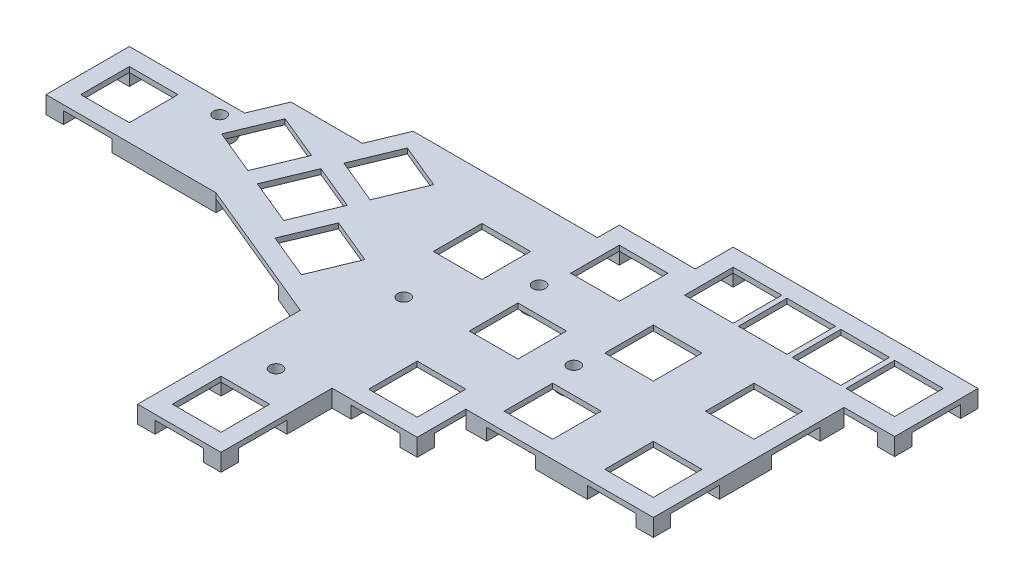
SolidWorks part; units mm, degrees
ref_plane "Front Plane" through (0, 0, 0) normal (0, 0, 1) x (1, 0, 0)
ref_plane "Top Plane" through (0, 0, 0) normal (0, 1, 0) x (1, 0, 0)
ref_plane "Right Plane" through (0, 0, 0) normal (1, 0, 0) x (0, 0, -1)
sketch "Button Reference" plane through (0, 0, 0) normal (0, 1, 0) x (1, 0, 0)
  line L0 (24.5, 61) -> (24.5, 32) construction
  line L1 (-36.2591, 48.1292) -> (-29.3708, 64.7591) construction
  line L2 (49.5, 75) -> (49.5, 46) construction
  line L3 (78.5, 75) -> (78.5, 46) construction
  line L4 (17.5, 0) -> (-17.5, 0) construction
  line L5 (-36.2591, 48.1292) -> (-19.6292, 41.2409) construction
  line L6 (17.5, -12.5) -> (-17.5, -12.5)
  line L7 (17.5, 12.5) -> (-17.5, 12.5)
  line L8 (24.6803, 89.9994) -> (49.5, 75) construction
  line L9 (24.6803, 89.9994) -> (24.5, 61) construction
  line L10 (-0.5241, 75.6559) -> (24.6803, 89.9994) construction
  line L11 (-0.5241, 75.6559) -> (24.5, 61) construction
  line L12 (-29.3708, 64.7591) -> (-12.7409, 57.8708) construction
  line L13 (-19.6292, 41.2409) -> (-12.7409, 57.8708) construction
  line L14 (-36.2591, 48.1292) -> (-12.7409, 57.8708) construction
  line L15 (-29.3708, 64.7591) -> (-19.6292, 41.2409) construction
  line L16 (-35.6984, 52.2266) -> (-28.8101, 68.8564) construction
  line L17 (-35.6984, 52.2266) -> (-52.3282, 59.1149) construction
  line L18 (-28.8101, 68.8564) -> (-45.4399, 75.7447) construction
  line L19 (-52.3282, 59.1149) -> (-45.4399, 75.7447) construction
  line L20 (-35.6984, 52.2266) -> (-45.4399, 75.7447) construction
  line L21 (-28.8101, 68.8564) -> (-52.3282, 59.1149) construction
  line L22 (-69.9281, 66.405) -> (-63.0398, 83.0348) construction
  line L23 (-69.9281, 66.405) -> (-53.2983, 59.5167) construction
  line L24 (-63.0398, 83.0348) -> (-46.41, 76.1465) construction
  line L25 (-53.2983, 59.5167) -> (-46.41, 76.1465) construction
  line L26 (-69.9281, 66.405) -> (-46.41, 76.1465) construction
  line L27 (-63.0398, 83.0348) -> (-53.2983, 59.5167) construction
  line L28 (-40.5692, 63.9856) -> (-22.9693, 56.6955) construction
  line L29 (-40.5692, 63.9856) -> (-58.1691, 71.2758) construction
  line L30 (-45.0381, 76.7148) -> (-38.1498, 93.3446) construction
  line L31 (-45.0381, 76.7148) -> (-28.4083, 69.8265) construction
  line L32 (-38.1498, 93.3446) -> (-21.52, 86.4563) construction
  line L33 (-28.4083, 69.8265) -> (-21.52, 86.4563) construction
  line L34 (-45.0381, 76.7148) -> (-21.52, 86.4563) construction
  line L35 (-38.1498, 93.3446) -> (-28.4083, 69.8265) construction
  line L36 (-40.5692, 63.9856) -> (-33.2791, 81.5855) construction
  line L37 (-24.5, 53) -> (-22.9693, 56.6955) construction
  line L38 (-58.1691, 71.2758) -> (-65.4592, 53.6759) construction
  line L39 (-65.4592, 53.6759) -> (-90.4039, 64.0083) construction
  line L40 (-70.5814, 66.1344) -> (-63.3104, 83.6881)
  line L41 (-63.3104, 83.6881) -> (-45.7105, 76.398)
  line L42 (-45.7105, 76.398) -> (-38.4204, 93.9979)
  line L43 (-38.4204, 93.9979) -> (-20.8667, 86.7269)
  line L44 (-20.8667, 86.7269) -> (-29.6876, 65.4315)
  line L45 (-29.6876, 65.4315) -> (-12.0877, 58.1414)
  line L46 (-12.0877, 58.1414) -> (-19.3586, 40.5877)
  line L47 (-19.3586, 40.5877) -> (-36.9123, 47.8586)
  line L48 (-36.9123, 47.8586) -> (-35.3816, 51.5542)
  line L49 (-35.3816, 51.5542) -> (-70.5814, 66.1344)
  line L50 (-66.484, 74.7199) -> (-66.9459, 74.9112) construction
  line L51 (-29.6436, 90.3624) -> (-29.8349, 89.9005) construction
  line L52 (-16.1851, 49.5558) -> (-15.7231, 49.3645) construction
  line L53 (-33.2791, 81.8539) -> (-33.2791, 81.5855) construction
  line L54 (46.566, 100.92) -> (46.566, 75) construction
  line L55 (46.566, 75) -> (49.5, 75) construction
  circle A0 centre (24.5, 32) radius 12.5
  circle A1 centre (24.5, 61) radius 12.5
  circle A2 centre (49.5, 46) radius 12.5
  circle A3 centre (49.5, 75) radius 12.5
  circle A4 centre (78.5, 75) radius 12.5
  circle A5 centre (78.5, 46) radius 12.5
  arc A6 (17.5, -12.5) -> (17.5, 12.5) centre (17.5, 0) ccw
  arc A7 (-17.5, 12.5) -> (-17.5, -12.5) centre (-17.5, 0) ccw
  circle A8 centre (-90.4039, 64.0083) radius 15.5
  circle A9 centre (24.6803, 89.9994) radius 12.5
  circle A10 centre (-0.5241, 75.6559) radius 12.5
  circle A11 centre (46.566, 100.92) radius 2.8
  circle A12 centre (62.066, 100.92) radius 2.8
  circle A13 centre (77.566, 100.92) radius 2.8
  circle A14 centre (93.066, 100.92) radius 2.8
  point P1 (-24.5, 53)
  point P3 (-40.5692, 63.9856)
  point P4 (-58.1691, 71.2758)
  point P35 (0, 0)
  point P43 (-33.2791, 81.5855)
  point P50 (-30, 0)
  point P51 (30, 0)
  dimension "D2" = 25
  dimension "D6" = 12.5
  dimension "D10" = 31
  dimension "D26" = 5.6
  dimension "D1" = 29
  dimension "D3" = 25
  dimension "D4" = 29
  dimension "D5" = 14
  dimension "D7" = 32
  dimension "D8" = 7
  dimension "D9" = 60
  dimension "D11" = 29
  dimension "D12" = 29
  dimension "D13" = 7
  dimension "D14" = 18
  dimension "D15" = 27
  dimension "D16" = 19.05
  dimension "D17" = 19.05
  dimension "D18" = 53
  dimension "D19" = 4
  dimension "D20" = 0.5
  dimension "D21" = 0.5
  dimension "D22" = 0.5
  dimension "D23" = 0.5
  dimension "D24" = 0.5
  dimension "D25" = 22.5
  dimension "D27" = 15.5
  dimension "D28" = 15.5
  dimension "D29" = 15.5
  dimension "D30" = 25.92
  dimension "D31" = 2.934
sketch "Sketch2" plane through (0, 0, 0) normal (0, 1, 0) x (1, 0, 0)
  line L0 (90.5, 34) -> (90.5, 88.92)
  line L1 (-97.4039, 57.0083) -> (-83.4039, 57.0083)
  line L2 (-97.4039, 57.0083) -> (-97.4039, 71.0083)
  line L3 (-97.4039, 71.0083) -> (-83.4039, 71.0083)
  line L4 (-83.4039, 57.0083) -> (-83.4039, 71.0083)
  line L5 (-97.4039, 57.0083) -> (-83.4039, 71.0083) construction
  line L6 (-97.4039, 71.0083) -> (-83.4039, 57.0083) construction
  line L11 (-67.315, 67.4874) -> (-61.9574, 80.4217)
  line L12 (-67.315, 67.4874) -> (-54.3807, 62.1298)
  line L17 (-61.9574, 80.4217) -> (-49.0231, 75.0641)
  line L18 (-54.3807, 62.1298) -> (-49.0231, 75.0641)
  line L23 (-67.315, 67.4874) -> (-49.0231, 75.0641) construction
  line L24 (-61.9574, 80.4217) -> (-54.3807, 62.1298) construction
  line L25 (53.566, 93.92) -> (39.566, 93.92)
  line L30 (-31.4232, 67.774) -> (-44.3575, 73.1316)
  line L31 (-31.4232, 67.774) -> (-36.7808, 54.8397)
  line L32 (53.566, 93.92) -> (53.566, 107.92)
  line L33 (-7.5241, 68.6559) -> (6.4759, 68.6559)
  line L34 (-7.5241, 68.6559) -> (-7.5241, 82.6559)
  line L35 (-7.5241, 82.6559) -> (6.4759, 82.6559)
  line L36 (6.4759, 68.6559) -> (6.4759, 82.6559)
  line L37 (-7.5241, 68.6559) -> (6.4759, 82.6559) construction
  line L38 (-7.5241, 82.6559) -> (6.4759, 68.6559) construction
  line L39 (17.6803, 82.9994) -> (31.6803, 82.9994)
  line L40 (17.6803, 82.9994) -> (17.6803, 96.9994)
  line L41 (17.6803, 96.9994) -> (31.6803, 96.9994)
  line L42 (31.6803, 82.9994) -> (31.6803, 96.9994)
  line L43 (17.6803, 82.9994) -> (31.6803, 96.9994) construction
  line L44 (17.6803, 96.9994) -> (31.6803, 82.9994) construction
  line L45 (17.5, 68) -> (31.5, 68)
  line L46 (17.5, 68) -> (17.5, 54)
  line L47 (17.5, 54) -> (31.5, 54)
  line L48 (31.5, 68) -> (31.5, 54)
  line L49 (17.5, 68) -> (31.5, 54) construction
  line L50 (17.5, 54) -> (31.5, 68) construction
  line L51 (17.5, 39) -> (31.5, 39)
  line L52 (17.5, 39) -> (17.5, 25)
  line L53 (17.5, 25) -> (31.5, 25)
  line L54 (31.5, 39) -> (31.5, 25)
  line L55 (17.5, 39) -> (31.5, 25) construction
  line L56 (17.5, 25) -> (31.5, 39) construction
  line L57 (42.5, 39) -> (56.5, 39)
  line L58 (42.5, 39) -> (42.5, 53)
  line L59 (42.5, 53) -> (56.5, 53)
  line L60 (56.5, 39) -> (56.5, 53)
  line L61 (42.5, 39) -> (56.5, 53) construction
  line L62 (42.5, 53) -> (56.5, 39) construction
  line L63 (42.5, 82) -> (56.5, 82)
  line L64 (42.5, 82) -> (42.5, 68)
  line L65 (42.5, 68) -> (56.5, 68)
  line L66 (56.5, 82) -> (56.5, 68)
  line L67 (42.5, 82) -> (56.5, 68) construction
  line L68 (42.5, 68) -> (56.5, 82) construction
  line L69 (71.5, 68) -> (85.5, 68)
  line L70 (71.5, 68) -> (71.5, 82)
  line L71 (71.5, 82) -> (85.5, 82)
  line L72 (85.5, 68) -> (85.5, 82)
  line L73 (71.5, 68) -> (85.5, 82) construction
  line L74 (71.5, 82) -> (85.5, 68) construction
  line L75 (71.5, 39) -> (85.5, 39)
  line L76 (71.5, 39) -> (71.5, 53)
  line L77 (71.5, 53) -> (85.5, 53)
  line L78 (85.5, 39) -> (85.5, 53)
  line L79 (71.5, 39) -> (85.5, 53) construction
  line L80 (71.5, 53) -> (85.5, 39) construction
  line L81 (-7, -7) -> (7, -7)
  line L82 (-7, -7) -> (-7, 7)
  line L83 (-7, 7) -> (7, 7)
  line L84 (7, -7) -> (7, 7)
  line L85 (-7, -7) -> (7, 7) construction
  line L86 (-7, 7) -> (7, -7) construction
  line L87 (53.566, 107.92) -> (39.566, 107.92)
  line L88 (-44.3575, 73.1316) -> (-49.7151, 60.1973)
  line L89 (-36.7808, 54.8397) -> (-49.7151, 60.1973)
  line L90 (-31.4232, 67.774) -> (-49.7151, 60.1973) construction
  line L91 (-44.3575, 73.1316) -> (-36.7808, 54.8397) construction
  line L92 (-33.6459, 49.2116) -> (-20.7116, 43.8541)
  line L93 (-33.6459, 49.2116) -> (-28.2884, 62.1459)
  line L94 (-20.7116, 43.8541) -> (-15.3541, 56.7884)
  line L95 (-28.2884, 62.1459) -> (-15.3541, 56.7884)
  line L96 (-33.6459, 49.2116) -> (-15.3541, 56.7884) construction
  line L97 (-20.7116, 43.8541) -> (-28.2884, 62.1459) construction
  line L98 (-42.425, 77.7972) -> (-37.0674, 90.7315)
  line L99 (-42.425, 77.7972) -> (-29.4907, 72.4396)
  line L100 (-37.0674, 90.7315) -> (-24.1331, 85.3739)
  line L101 (-29.4907, 72.4396) -> (-24.1331, 85.3739)
  line L102 (-42.425, 77.7972) -> (-24.1331, 85.3739) construction
  line L103 (-37.0674, 90.7315) -> (-29.4907, 72.4396) construction
  line L104 (-28.8101, 68.8564) -> (-45.4399, 75.7447) construction
  line L105 (39.566, 93.92) -> (39.566, 107.92)
  line L106 (53.566, 93.92) -> (39.566, 107.92) construction
  line L107 (53.566, 107.92) -> (39.566, 93.92) construction
  line L108 (55.066, 93.92) -> (69.066, 93.92)
  line L109 (55.066, 93.92) -> (55.066, 107.92)
  line L110 (55.066, 107.92) -> (69.066, 107.92)
  line L111 (69.066, 93.92) -> (69.066, 107.92)
  line L112 (55.066, 93.92) -> (69.066, 107.92) construction
  line L113 (55.066, 107.92) -> (69.066, 93.92) construction
  line L114 (70.566, 93.92) -> (84.566, 93.92)
  line L115 (70.566, 93.92) -> (70.566, 107.92)
  line L116 (70.566, 107.92) -> (84.566, 107.92)
  line L117 (84.566, 93.92) -> (84.566, 107.92)
  line L118 (70.566, 93.92) -> (84.566, 107.92) construction
  line L119 (70.566, 107.92) -> (84.566, 93.92) construction
  line L120 (86.066, 93.92) -> (100.066, 93.92)
  line L121 (86.066, 93.92) -> (86.066, 107.92)
  line L122 (86.066, 107.92) -> (100.066, 107.92)
  line L123 (100.066, 93.92) -> (100.066, 107.92)
  line L124 (86.066, 93.92) -> (100.066, 107.92) construction
  line L125 (86.066, 107.92) -> (100.066, 93.92) construction
  line L126 (105.066, 112.92) -> (34.566, 112.92)
  line L128 (12, -12) -> (-12, -12)
  line L129 (-102.4039, 76.0083) -> (-102.4039, 52.0083)
  line L130 (90.5, 88.92) -> (105.066, 88.92)
  line L131 (90.5, 34) -> (36.5, 34)
  line L132 (36.5, 34) -> (36.5, 20)
  line L133 (36.5, 20) -> (12, 20)
  line L134 (12, 20) -> (12, -12)
  line L135 (105.066, 112.92) -> (105.066, 88.92)
  line L136 (34.566, 112.92) -> (34.566, 101.9994)
  line L137 (34.566, 101.9994) -> (12.6803, 101.9994)
  line L138 (-40.4083, 95.7315) -> (-44.6788, 85.4217)
  line L139 (-44.6788, 85.4217) -> (-65.2983, 85.4217)
  line L140 (-65.2983, 85.4217) -> (-69.1975, 76.0083)
  line L141 (-69.1975, 76.0083) -> (-102.4039, 76.0083)
  line L142 (-12, -12) -> (-12, 34.8336)
  line L143 (-12, 34.8336) -> (-53.4633, 52.0083)
  line L144 (-53.4633, 52.0083) -> (-102.4039, 52.0083)
  line L145 (-40.4083, 95.7315) -> (12.6803, 95.7315)
  line L146 (12.6803, 95.7315) -> (12.6803, 101.9994)
  point P0 (-90.4039, 64.0083)
  point P6 (46.566, 100.92)
  point P7 (-58.1691, 71.2758)
  point P8 (-40.5692, 63.9856)
  point P9 (-24.5, 53)
  point P15 (-33.2791, 81.5855)
  point P31 (62.066, 100.92)
  point P32 (-0.5241, 75.6559)
  point P38 (24.6803, 89.9994)
  point P44 (24.5, 61)
  point P50 (24.5, 32)
  point P56 (49.5, 46)
  point P62 (49.5, 75)
  point P68 (78.5, 75)
  point P74 (78.5, 46)
  point P80 (0, 0)
  point P98 (77.566, 100.92)
  point P104 (93.066, 100.92)
  dimension "D1" = 14
  dimension "D2" = 5
  dimension "D3" = 5
  dimension "D4" = 5
  dimension "D5" = 5
  dimension "D6" = 5
  dimension "D7" = 5
  dimension "D8" = 5
  dimension "D9" = 5
  dimension "D10" = 5
  dimension "D11" = 5
  dimension "D12" = 5
  dimension "D13" = 5
  dimension "D14" = 5
  dimension "D15" = 5
  dimension "D16" = 5
  dimension "D17" = 5
  dimension "D18" = 5
  dimension "D19" = 5
  dimension "D20" = 5
  dimension "D21" = 5
  dimension "D22" = 5
extrude "Boss-Extrude1" add sketch "Sketch2" along normal blind 1.5
sketch "Sketch3" plane through (0, 0, 0) normal (0, -1, 0) x (1, 0, 0)
  line L0 (-20.7116, -43.8541) -> (-22.625, -39.2347)
  line L1 (34.566, -112.92) -> (39.566, -112.92)
  line L2 (34.566, -112.92) -> (34.566, -107.92)
  line L3 (34.566, -107.92) -> (39.566, -107.92)
  line L4 (39.566, -112.92) -> (39.566, -107.92)
  line L5 (100.066, -107.92) -> (105.066, -107.92)
  line L6 (100.066, -107.92) -> (100.066, -112.92)
  line L7 (100.066, -112.92) -> (105.066, -112.92)
  line L8 (105.066, -107.92) -> (105.066, -112.92)
  line L9 (100.066, -93.92) -> (105.066, -93.92)
  line L10 (100.066, -93.92) -> (100.066, -88.92)
  line L11 (100.066, -88.92) -> (105.066, -88.92)
  line L12 (105.066, -93.92) -> (105.066, -88.92)
  line L13 (90.5, -34) -> (85.5, -34)
  line L14 (90.5, -34) -> (90.5, -39)
  line L15 (90.5, -39) -> (85.5, -39)
  line L16 (85.5, -34) -> (85.5, -39)
  line L17 (36.5, -20) -> (31.5, -20)
  line L18 (36.5, -20) -> (36.5, -25)
  line L19 (36.5, -25) -> (31.5, -25)
  line L20 (31.5, -20) -> (31.5, -25)
  line L21 (12, 12) -> (7, 12)
  line L22 (12, 12) -> (12, 7)
  line L23 (12, 7) -> (7, 7)
  line L24 (7, 12) -> (7, 7)
  line L25 (-7, 7) -> (-12, 7)
  line L26 (-7, 7) -> (-7, 12)
  line L27 (-7, 12) -> (-12, 12)
  line L28 (-12, 7) -> (-12, 12)
  line L29 (-102.4039, -52.0083) -> (-97.4039, -52.0083)
  line L30 (-102.4039, -52.0083) -> (-102.4039, -57.0083)
  line L31 (-102.4039, -57.0083) -> (-97.4039, -57.0083)
  line L32 (-97.4039, -52.0083) -> (-97.4039, -57.0083)
  line L33 (-97.4039, -71.0083) -> (-102.4039, -71.0083)
  line L34 (-97.4039, -71.0083) -> (-97.4039, -76.0083)
  line L35 (-97.4039, -76.0083) -> (-102.4039, -76.0083)
  line L36 (-102.4039, -71.0083) -> (-102.4039, -76.0083)
  line L37 (-20.7116, -43.8541) -> (-12, -40.2456)
  line L38 (-22.625, -39.2347) -> (-12, -34.8336)
  line L40 (-53.4633, -52.0083) -> (-12, -34.8336) construction
  line L42 (17.5, -25) -> (7, -25)
  line L43 (17.5, -25) -> (17.5, -20)
  line L44 (17.5, -20) -> (12, -20)
  line L51 (-102.4039, -52.0083) -> (-53.4633, -52.0083) construction
  line L52 (-83.4039, -57.0083) -> (-53.4633, -57.0083)
  line L53 (-83.4039, -57.0083) -> (-83.4039, -52.0083)
  line L54 (-83.4039, -52.0083) -> (-53.4633, -52.0083)
  line L55 (-53.4633, -57.0083) -> (-53.4633, -52.0083)
  line L56 (-38.4204, -93.9979) -> (-20.8667, -86.7269) construction
  line L57 (17.6803, -96.9994) -> (12.6803, -96.9994)
  line L58 (36.5, -34) -> (90.5, -34) construction
  line L59 (-83.4039, -71.0083) -> (-76.2052, -71.0083)
  line L60 (-83.4039, -71.0083) -> (-83.4039, -76.0083)
  line L61 (-83.4039, -76.0083) -> (-69.1975, -76.0083)
  line L62 (-69.1975, -74.2697) -> (-69.1975, -76.0083)
  line L63 (-7, -7) -> (-12, -7)
  line L64 (-7, -7) -> (-7, -40.2456)
  line L67 (7, -7) -> (12, -7)
  line L68 (7, -7) -> (7, -25)
  line L70 (12, -7) -> (12, -20)
  line L71 (36.5, -34) -> (42.5, -34)
  line L72 (36.5, -34) -> (36.5, -39)
  line L73 (36.5, -39) -> (42.5, -39)
  line L74 (42.5, -34) -> (42.5, -39)
  line L75 (56.5, -39) -> (71.5, -39)
  line L76 (56.5, -39) -> (56.5, -34)
  line L77 (56.5, -34) -> (71.5, -34)
  line L78 (71.5, -39) -> (71.5, -34)
  line L79 (90.5, -34) -> (90.5, -88.92) construction
  line L80 (85.5, -53) -> (90.5, -53)
  line L81 (85.5, -53) -> (85.5, -68)
  line L82 (85.5, -68) -> (90.5, -68)
  line L83 (90.5, -53) -> (90.5, -68)
  line L85 (34.566, -101.9994) -> (31.6803, -101.9994)
  line L86 (34.566, -101.9994) -> (34.566, -96.9994)
  line L87 (34.566, -96.9994) -> (31.6803, -96.9994)
  line L88 (31.6803, -101.9994) -> (31.6803, -96.9994)
  line L89 (85.5, -82) -> (90.5, -82)
  line L90 (85.5, -82) -> (85.5, -88.92)
  line L91 (85.5, -88.92) -> (90.5, -88.92)
  line L92 (90.5, -82) -> (90.5, -88.92)
  line L93 (-7, -40.2456) -> (-12, -40.2456)
  line L94 (-12, -7) -> (-12, -34.8336)
  line L95 (-70.5814, -66.1344) -> (-63.3104, -83.6881) construction
  line L96 (17.5, -12.5) -> (-17.5, -12.5) construction
  line L97 (17.6803, -96.9994) -> (17.6803, -101.9994)
  line L98 (17.6803, -101.9994) -> (12.6803, -101.9994)
  line L99 (12.6803, -96.9994) -> (12.6803, -101.9994)
  line L100 (12.6803, -95.7315) -> (-35.363, -95.7315)
  line L101 (12.6803, -95.7315) -> (12.6803, -92.7315)
  line L102 (12.6803, -92.7315) -> (-35.363, -92.7315)
  line L103 (-35.363, -95.7315) -> (-35.363, -92.7315)
  circle A0 centre (-0.4039, -53) radius 7.5
  circle A1 centre (-0.9039, -16.75) radius 4.25
  circle A2 centre (41.0961, -60.5) radius 4.2594
  circle A3 centre (16.0961, -75.5) radius 4.2594
  arc A4 (-69.1975, -74.2697) -> (-76.2052, -71.0083) centre (-72.4039, -72) ccw
  circle A5 centre (24.5, -61) radius 12.5 construction
  circle A6 centre (49.5, -46) radius 12.5 construction
  point P69 (-0.9039, -16.75)
  point P73 (41.0961, -60.5)
  point P158 (-72.4039, -72)
  dimension "D1" = 15
  dimension "D2" = 3
extrude "Boss-Extrude2" add sketch "Sketch3" along normal blind 3.5
hole_wizard "M3 Clearance Hole1" positions "3DSketch1" profile "Sketch5" hole size "M3" standard "ANSI Metric" end condition up to next
sketch3d "3DSketch1"
  line L0 (-0.4039, -3.5, -53) -> (-0.4039, 0, -53) construction
  line L1 (16.0961, -3.5, -75.5) -> (16.0961, 0, -75.5) construction
  line L2 (-0.9039, -3.5, -16.75) -> (-0.9039, 0, -16.75) construction
  line L3 (41.0961, -3.5, -60.5) -> (41.0961, 0, -60.5) construction
  line L4 (-72.4039, -3.5, -72) -> (-72.4039, 0, -72) construction
  point P0 (-0.4039, -3.5, -53)
  point P4 (41.0961, -3.5, -60.5)
  point P6 (16.0961, -3.5, -75.5)
  point P10 (-0.9039, -3.5, -16.75)
  point P18 (-72.4039, -3.5, -72)
sketch "Sketch5" plane through (-0.4039, -3.5, -53) normal (1, 0, 0) x (0, 0, -1)
  line L0 (0, 0) -> (0, 5)
  line L1 (0, 5) -> (1.8, 5)
  line L2 (1.8, 5) -> (1.8, 0.025)
  line L3 (1.8, 0.025) -> (1.825, 0)
  line L5 (1.825, 0) -> (0, 0)
  line L6 (-1.8, 0.025) -> (-1.825, 0) construction
  line L11 (0, -6.35) -> (0, 107.95) construction
  dimension "Thru Hole Dia." = 3.6
  dimension "Thru Hole Depth" = 5
  dimension "Near C'Sink Dia." = 3.65
  dimension "Near C'Sink Angle" = 90
